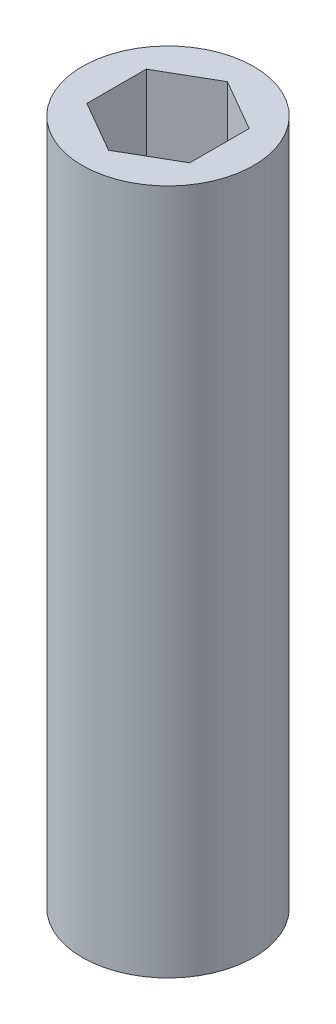
SolidWorks part; units mm, degrees
ref_plane "前视基准面" through (0, 0, 0) normal (0, 0, 1) x (1, 0, 0)
ref_plane "上视基准面" through (0, 0, 0) normal (0, 1, 0) x (1, 0, 0)
ref_plane "右视基准面" through (0, 0, 0) normal (1, 0, 0) x (0, 0, -1)
sketch "草图1" plane through (0, 0, 0) normal (0, 1, 0) x (1, 0, 0)
  circle A0 centre (0, 0) radius 10
  circle A1 centre (0, 0) radius 4
  dimension "D1" = 20
  dimension "D2" = 8
extrude "凸台-拉伸1" add sketch "草图1" along normal blind 80
sketch "草图2" plane through (0, 80, 0) normal (0, 1, 0) x (1, 0, 0)
  line L1 (0, -6.9282) -> (6, -3.4641)
  line L2 (6, -3.4641) -> (6, 3.4641)
  line L3 (6, 3.4641) -> (0, 6.9282)
  line L4 (0, 6.9282) -> (-6, 3.4641)
  line L5 (-6, 3.4641) -> (-6, -3.4641)
  line L6 (-6, -3.4641) -> (0, -6.9282)
  circle A0 centre (0, 0) radius 6 construction
  dimension "D1" = 12
extrude "切除-拉伸1" cut sketch "草图2" against normal blind 18
